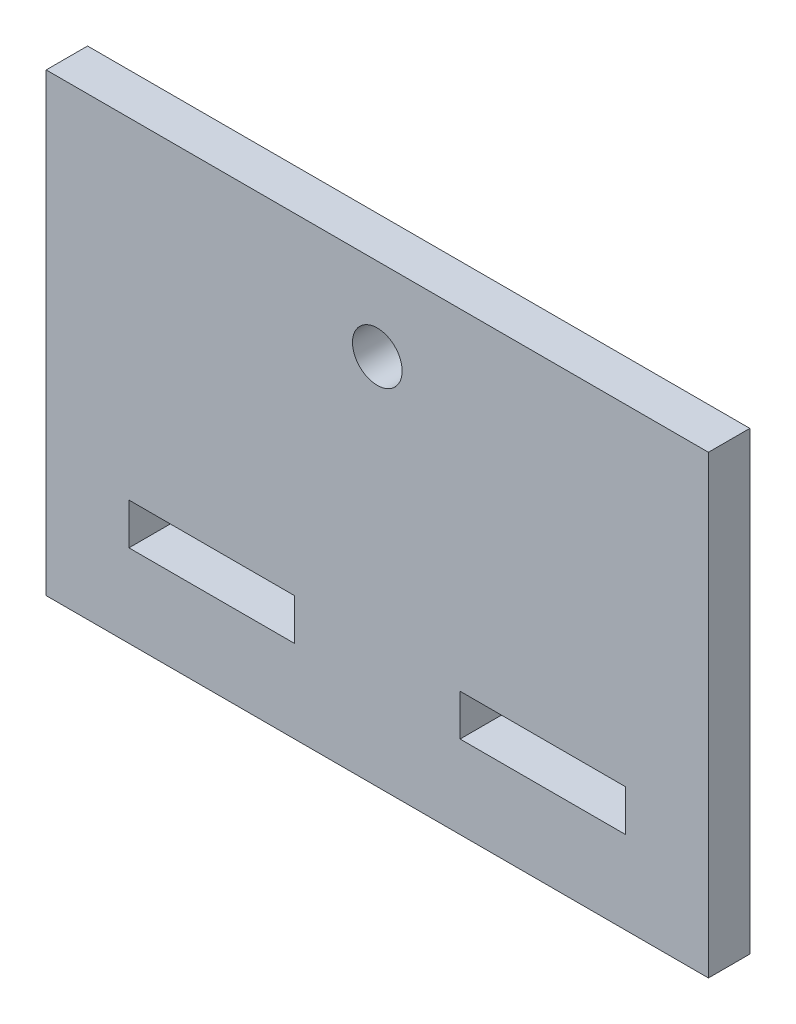
SolidWorks part; units mm, degrees
ref_plane "Front Plane" through (0, 0, 0) normal (0, 0, 1) x (1, 0, 0)
ref_plane "Top Plane" through (0, 0, 0) normal (0, 1, 0) x (1, 0, 0)
ref_plane "Right Plane" through (0, 0, 0) normal (1, 0, 0) x (0, 0, -1)
sketch "Sketch1" plane through (0, 0, 0) normal (0, 0, 1) x (1, 0, 0)
  line L0 (0, 0) -> (50.8, 0)
  line L1 (50.8, 0) -> (50.8, 34.925)
  line L2 (50.8, 34.925) -> (0, 34.925)
  line L3 (0, 34.925) -> (0, 0)
  line L4 (25.4, 34.925) -> (25.4, 28.575) construction
  line L5 (6.35, 6.35) -> (19.05, 6.35)
  line L6 (6.35, 6.35) -> (6.35, 9.525)
  line L7 (6.35, 9.525) -> (19.05, 9.525)
  line L8 (19.05, 6.35) -> (19.05, 9.525)
  line L9 (31.75, 6.35) -> (44.45, 6.35)
  line L10 (31.75, 6.35) -> (31.75, 9.525)
  line L11 (31.75, 9.525) -> (44.45, 9.525)
  line L12 (44.45, 6.35) -> (44.45, 9.525)
  circle A0 centre (25.4, 28.575) radius 1.905
  dimension "D7" = 3.81
  dimension "D1" = 3.175
  dimension "D2" = 12.7
  dimension "D3" = 50.8
  dimension "D4" = 6.35
  dimension "D5" = 12.7
  dimension "D6" = 6.35
  dimension "D8" = 19.05
  dimension "D9" = 25.4
extrude "Boss-Extrude1" add sketch "Sketch1" along normal blind 3.175
